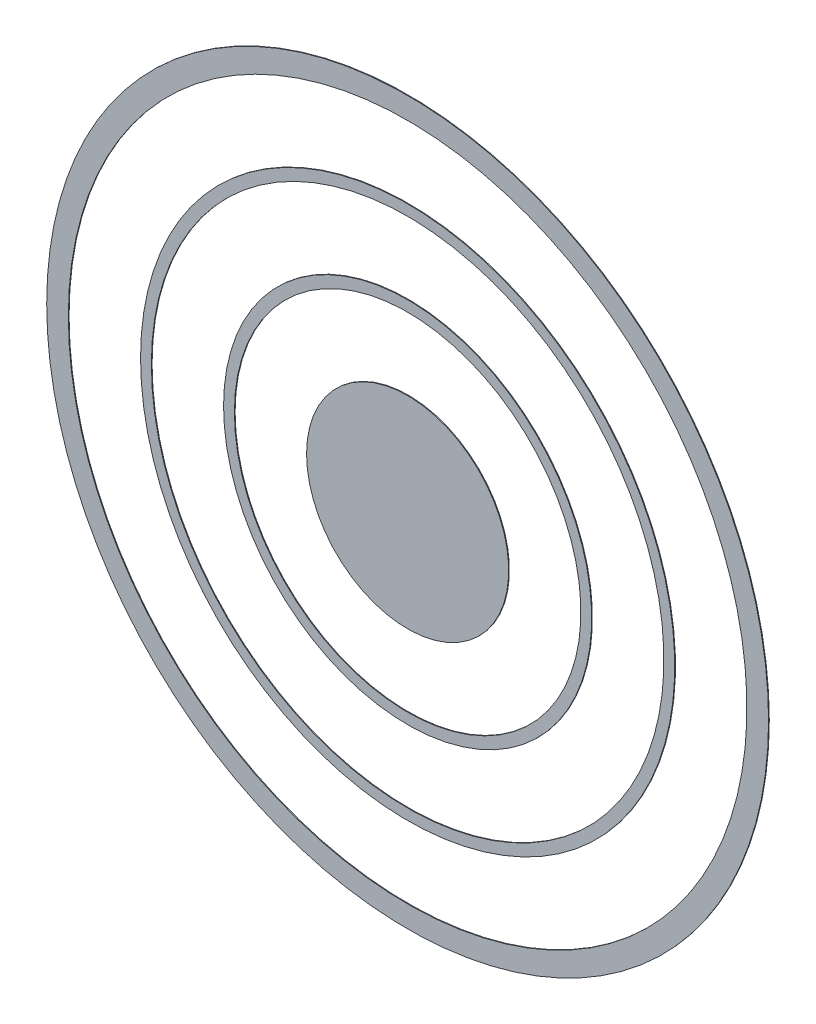
SolidWorks part; units mm, degrees
material "ABS"
ref_plane "Front" through (0, 0, 0) normal (0, 0, 1) x (1, 0, 0)
ref_plane "Top" through (0, 0, 0) normal (0, 1, 0) x (1, 0, 0)
ref_plane "Right" through (0, 0, 0) normal (1, 0, 0) x (0, 0, -1)
sketch "Эскиз1" plane through (0, 0, 0) normal (0, 0, 1) x (1, 0, 0)
  circle A0 centre (0, 0) radius 5
  circle A1 centre (0, 0) radius 4.7
  circle A2 centre (0, 0) radius 3.7
  circle A3 centre (0, 0) radius 3.55
  circle A4 centre (0, 0) radius 1.4
  circle A5 centre (0, 0) radius 2.4
  circle A6 centre (0, 0) radius 2.55
  dimension "D1" = 10
  dimension "D2" = 0.3
  dimension "D3" = 0.15
  dimension "D4" = 1
  dimension "D5" = 1
  dimension "D6" = 0.15
  dimension "D7" = 1
extrude "Бобышка-Вытянуть1" add sketch "Эскиз1" along normal blind 0.01 contours A0 A1 | A2 A3 | A6 A5 | A4
sketch "Эскиз2" plane through (0, 0, 0) normal (0, 0, 1) x (1, 0, 0)
  text T0 "Touch\r\n  Key" font "Century Gothic" height 1.5
